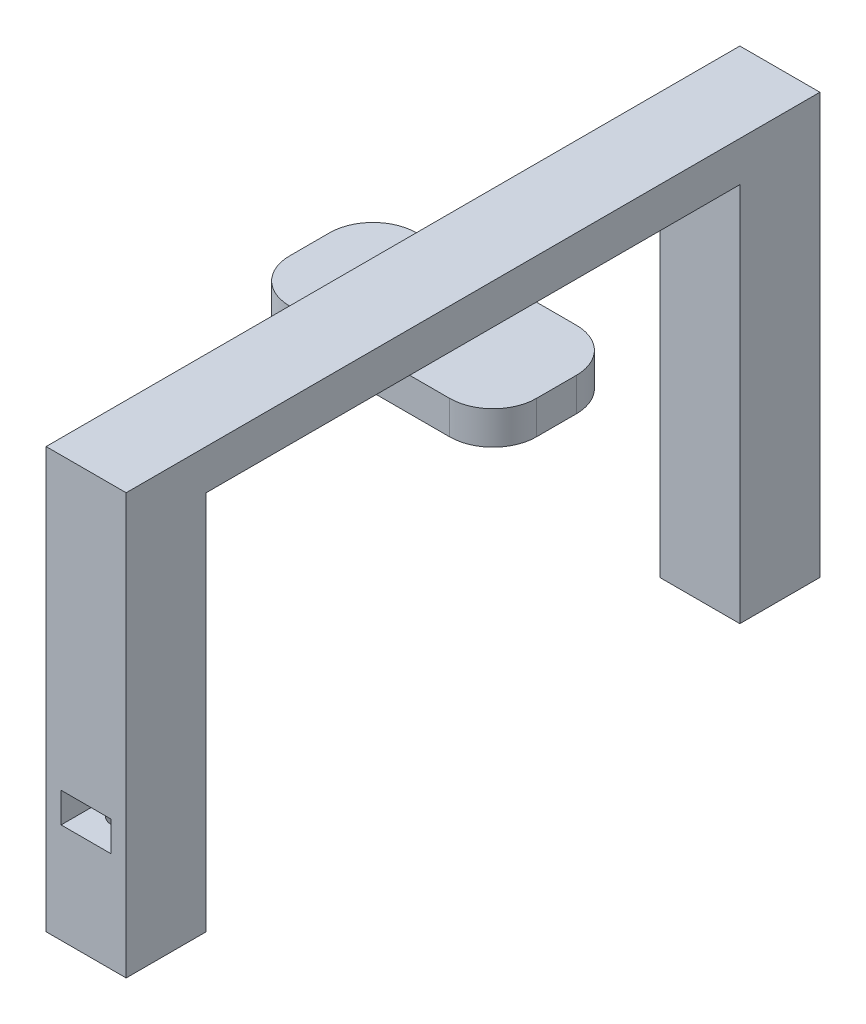
SolidWorks part; units mm, degrees
ref_plane "Plan de face" through (0, 0, 0) normal (0, 0, 1) x (1, 0, 0)
ref_plane "Plan de dessus" through (0, 0, 0) normal (0, 1, 0) x (1, 0, 0)
ref_plane "Plan de droite" through (0, 0, 0) normal (1, 0, 0) x (0, 0, -1)
sketch "Esquisse1" plane through (0, 0, 0) normal (0, 1, 0) x (1, 0, 0)
  line L1 (-23.3674, 11.4324) -> (13.6326, 11.4324)
  line L2 (-23.3674, 11.4324) -> (-23.3674, -7.5676)
  line L3 (-23.3674, -7.5676) -> (13.6326, -7.5676)
  line L4 (13.6326, 11.4324) -> (13.6326, -7.5676)
  dimension "D1" = 37
  dimension "D2" = 19
extrude "Boss.-Extru.1" add sketch "Esquisse1" along normal blind 5
fillet "Congé1" radius 6.5 4 edges at (-23.3674, 2.5, -11.4324) (13.6326, 2.5, -11.4324) (13.6326, 2.5, 7.5676) (-23.3674, 2.5, 7.5676)
sketch "Esquisse4" plane through (0, 5, 0) normal (0, 1, 0) x (1, 0, 0)
  line L0 (-16.8674, -7.5676) -> (7.1326, -7.5676) construction
  line L1 (-10.8674, -50.0676) -> (1.1326, -50.0676)
  line L2 (-10.8674, -50.0676) -> (-10.8674, 53.9324)
  line L3 (-10.8674, 53.9324) -> (1.1326, 53.9324)
  line L4 (1.1326, -50.0676) -> (1.1326, 53.9324)
  line L5 (13.6326, -1.0676) -> (13.6326, 4.9324) construction
  dimension "D1" = 104
  dimension "D2" = 42.5
  dimension "D3" = 12
  dimension "D4" = 12.5
extrude "Boss.-Extru.2" add sketch "Esquisse4" along normal blind 6 contours L2 L3 L4 L1
sketch "Esquisse5" plane through (0, 5, 0) normal (0, -1, 0) x (-1, 0, 0)
  line L0 (10.8674, 11.4324) -> (10.8674, 53.9324) construction
  line L1 (-1.1326, 53.9324) -> (10.8674, 53.9324)
  line L2 (-1.1326, 53.9324) -> (-1.1326, 41.9324)
  line L3 (-1.1326, 41.9324) -> (10.8674, 41.9324)
  line L4 (10.8674, 53.9324) -> (10.8674, 41.9324)
  line L5 (10.8674, -50.0676) -> (10.8674, -7.5676) construction
  line L6 (-1.1326, -50.0676) -> (10.8674, -50.0676)
  line L7 (-1.1326, -50.0676) -> (-1.1326, -38.0676)
  line L8 (-1.1326, -38.0676) -> (10.8674, -38.0676)
  line L9 (10.8674, -50.0676) -> (10.8674, -38.0676)
  line M1 (-1.1326, 53.9324) -> (-1.1326, 11.4324)
  line M3 (10.8674, 11.4324) -> (10.8674, 53.9324)
  line M4 (10.8674, 53.9324) -> (-1.1326, 53.9324)
  dimension "D1" = 12
  dimension "D2" = 12
extrude "Boss.-Extru.3" add sketch "Esquisse5" along normal blind 57 contours L3 M1 M3 M4 | L8 L9 L6 L7
sketch "Esquisse6" plane through (0, -52, 0) normal (0, -1, 0) x (1, 0, 0)
  line L0 (1.1326, 50.0676) -> (1.1326, 38.0676) construction
  line L2 (1.1326, 50.0676) -> (-10.8674, 50.0676) construction
  line L3 (1.1326, -53.9324) -> (1.1326, -41.9324) construction
  line L4 (1.1326, -41.9324) -> (-10.8674, -41.9324) construction
  circle A0 centre (-4.8674, 44.0676) radius 2.2
  circle A1 centre (-4.8674, -47.9324) radius 2.2
  dimension "D1" = 4.4
  dimension "D2" = 4.4
  dimension "D3" = 6
  dimension "D4" = 6
  dimension "D5" = 6
  dimension "D6" = 6
extrude "Enlèv. mat.-Extru.1" cut sketch "Esquisse6" against normal blind 40 contours A0 | A1
sketch "Esquisse7" plane through (0, 0, 50.0676) normal (0, 0, 1) x (1, 0, 0)
  line L0 (1.1326, -52) -> (-10.8674, -52) construction
  line L1 (-1.1174, -37) -> (-8.6174, -37)
  line L2 (-1.1174, -37) -> (-1.1174, -32.5)
  line L3 (-1.1174, -32.5) -> (-8.6174, -32.5)
  line L4 (-8.6174, -37) -> (-8.6174, -32.5)
  line L5 (-10.8674, 11) -> (-10.8674, -52) construction
  dimension "D1" = 15
  dimension "D2" = 7.5
  dimension "D3" = 2.25
  dimension "D4" = 4.5
extrude "Enlèv. mat.-Extru.2" cut sketch "Esquisse7" against normal blind 10.5 contours L1 L4 L3 L2
sketch "Esquisse8" plane through (0, 0, -53.9324) normal (0, 0, -1) x (-1, 0, 0)
  line L0 (10.8674, -52) -> (-1.1326, -52) construction
  line L1 (8.6174, -37) -> (1.1174, -37)
  line L2 (8.6174, -37) -> (8.6174, -32.5)
  line L3 (8.6174, -32.5) -> (1.1174, -32.5)
  line L4 (1.1174, -37) -> (1.1174, -32.5)
  line L5 (10.8674, 11) -> (10.8674, -52) construction
  dimension "D1" = 15
  dimension "D2" = 4.5
  dimension "D3" = 7.5
  dimension "D4" = 2.25
extrude "Enlèv. mat.-Extru.3" cut sketch "Esquisse8" against normal blind 10.5 contours L1 L4 L3 L2
equation "\"c1@Esquisse2\" = 20"
equation "\"D2@Esquisse4\"=(80+12+12-19)/2"
equation "\"D4@Esquisse4\"=(37-12)/2"
equation "\"D1@Boss.-Extru.3\"=58-1"
equation "\"D3@Esquisse7\"=(12-7.5)/2"
equation "\"D1@Esquisse4\"=80+12+12"
